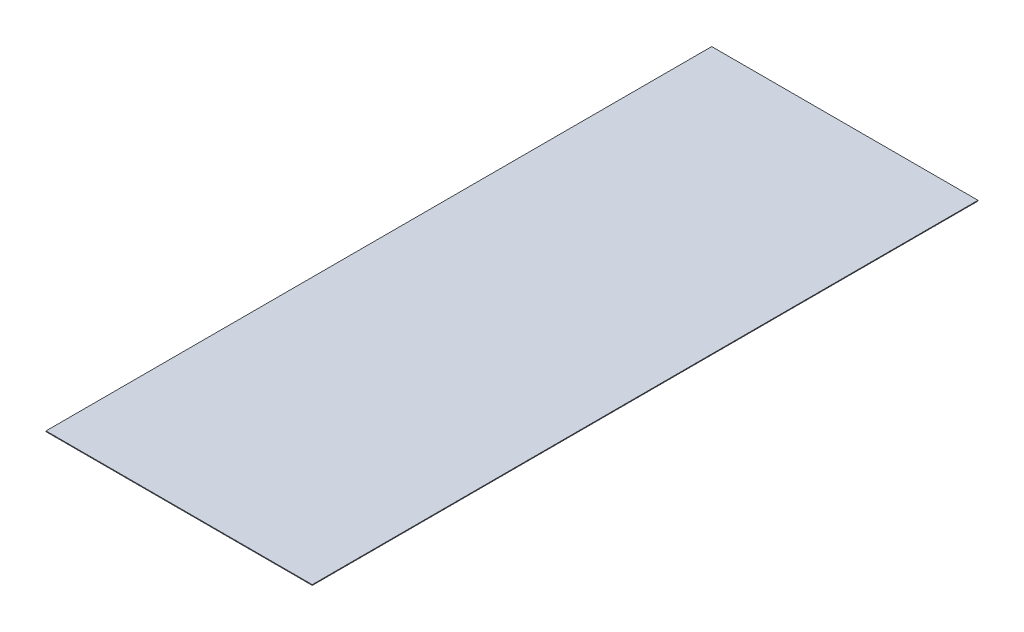
SolidWorks part; units mm, degrees
material "ASTM A36 Acero"
ref_plane "Alzado" through (0, 0, 0) normal (0, 0, 1) x (1, 0, 0)
ref_plane "Planta" through (0, 0, 0) normal (0, 1, 0) x (1, 0, 0)
ref_plane "Vista lateral" through (0, 0, 0) normal (1, 0, 0) x (0, 0, -1)
sketch "Croquis1" plane through (0, 0, 0) normal (0, 1, 0) x (1, 0, 0)
  line L1 (-609.6, -1524) -> (609.6, -1524)
  line L2 (-609.6, -1524) -> (-609.6, 1524)
  line L3 (-609.6, 1524) -> (609.6, 1524)
  line L4 (609.6, -1524) -> (609.6, 1524)
  line L5 (-609.6, -1524) -> (609.6, 1524) construction
  line L6 (-609.6, 1524) -> (609.6, -1524) construction
  point P0 (0, 0)
  dimension "D1" = 3048
  dimension "D2" = 1219.2
extrude "Saliente-Extruir1" add sketch "Croquis1" along normal blind 3.2
